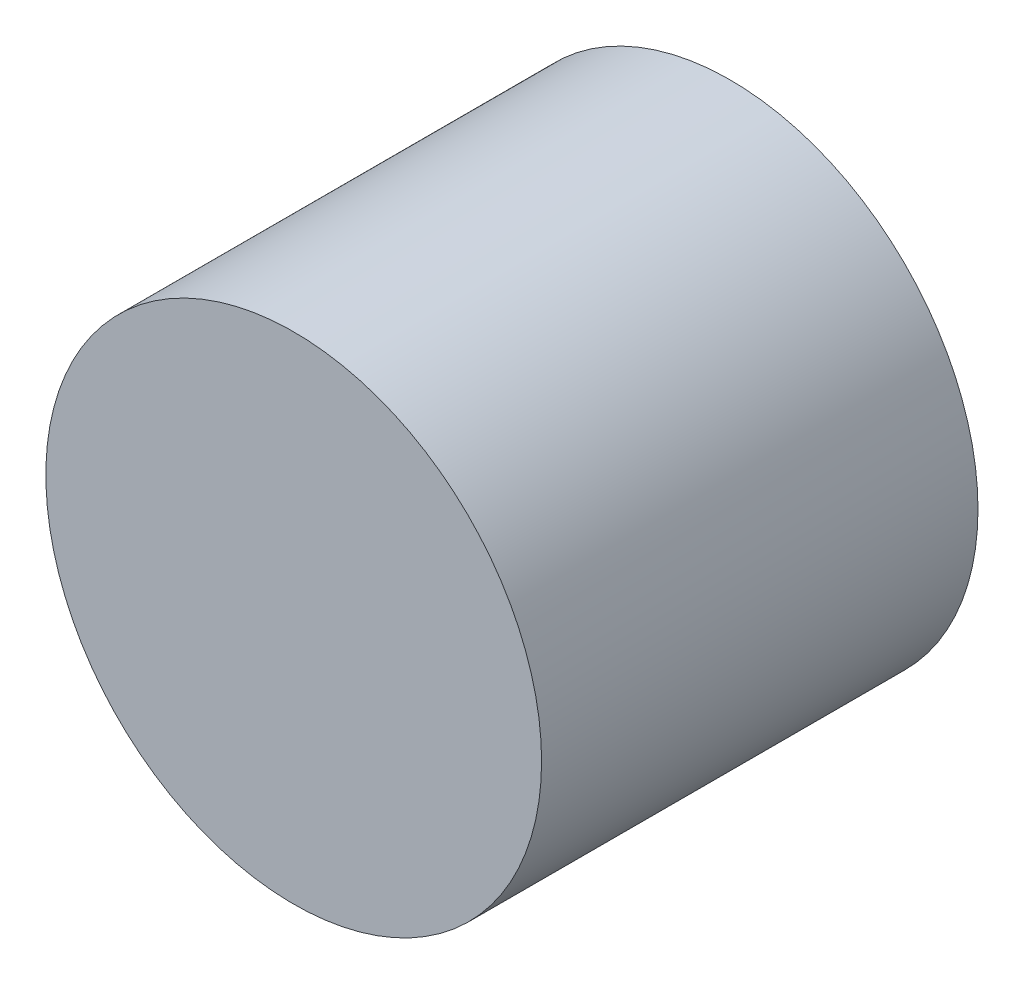
SolidWorks part; units mm, degrees
ref_plane "Ebene vorne" through (0, 0, 0) normal (0, 0, 1) x (1, 0, 0)
ref_plane "Ebene oben" through (0, 0, 0) normal (0, 1, 0) x (1, 0, 0)
ref_plane "Ebene rechts" through (0, 0, 0) normal (1, 0, 0) x (0, 0, -1)
sketch "Skizze1" plane through (0, 0, 0) normal (0, 0, 1) x (1, 0, 0)
  circle A0 centre (17.0042, 109.6946) radius 45.4385 construction
  circle A1 centre (17.0042, 109.6946) radius 45.4385
extrude "Aufsatz-Linear austragen1" add sketch "Skizze1" along normal blind 80
